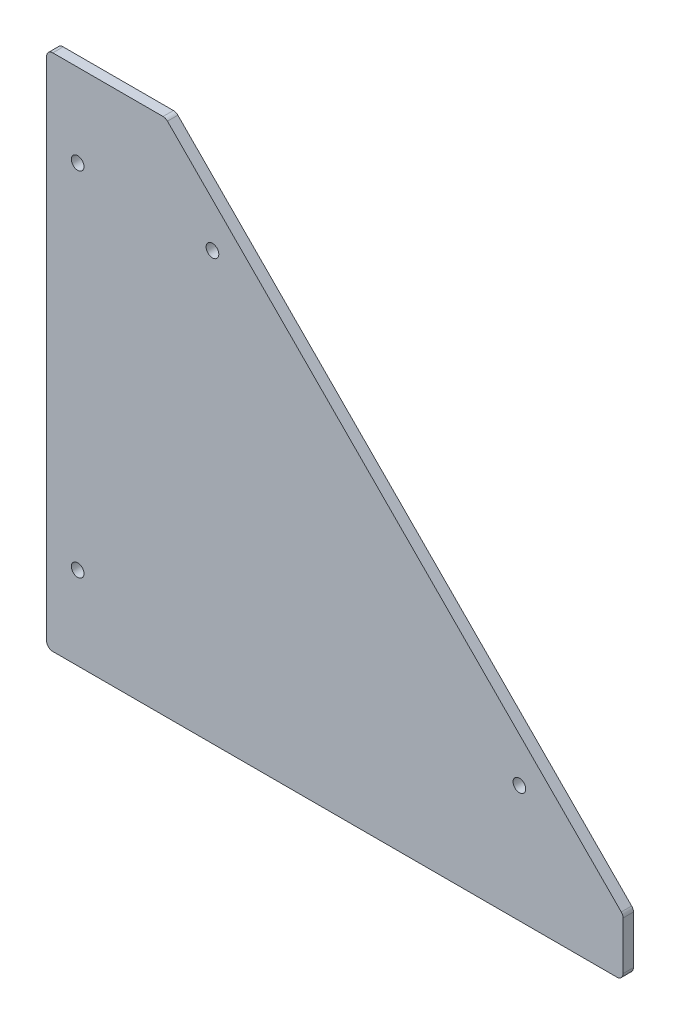
SolidWorks part; units mm, degrees
ref_plane "Front Plane" through (0, 0, 0) normal (0, 0, 1) x (1, 0, 0)
ref_plane "Top Plane" through (0, 0, 0) normal (0, 1, 0) x (1, 0, 0)
ref_plane "Right Plane" through (0, 0, 0) normal (1, 0, 0) x (0, 0, -1)
sketch "Sketch1" plane through (0, 0, 0) normal (0, 0, 1) x (1, 0, 0)
  line L0 (0, 0) -> (0, 250)
  line L2 (278, 0) -> (0, 0)
  line L3 (0, 250) -> (57.43, 250)
  line L4 (57.43, 250) -> (278, 27.43)
  line L5 (278, 27.43) -> (278, 0)
  line L6 (44.4484, 241.7897) -> (268.4363, 15.7708) construction
  circle A0 centre (15, 210) radius 3.05
  circle A1 centre (15, 40) radius 3.05
  circle A2 centre (80, 205.9158) radius 3.05
  circle A3 centre (228, 56.5738) radius 3.05
  dimension "D6" = 6.1
  dimension "D7" = 40
  dimension "D10" = 6.1
  dimension "D11" = 6.1
  dimension "D1" = 278
  dimension "D2" = 250
  dimension "D3" = 57.43
  dimension "D4" = 27.43
  dimension "D5" = 15
  dimension "D8" = 40
  dimension "D9" = 15
  dimension "D12" = 50
  dimension "D13" = 80
extrude "Boss-Extrude1" add sketch "Sketch1" along normal blind 5
fillet "Fillet1" radius 3 5 edges at (278, 27.43, 2.5) (278, 0, 2.5) (0, 0, 2.5) (0, 250, 2.5) (57.43, 250, 2.5)
